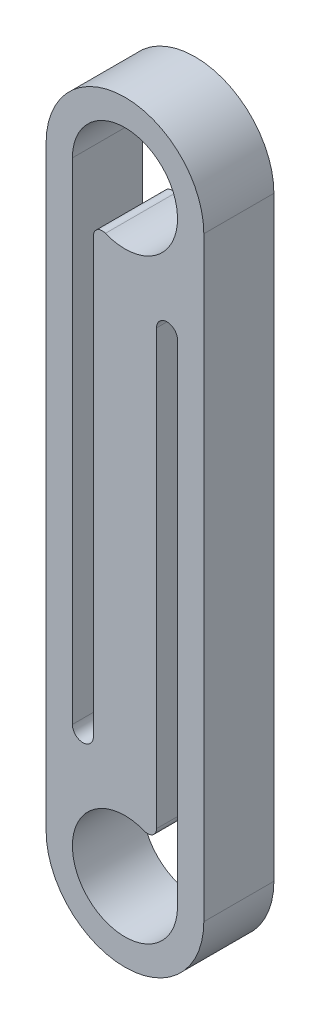
SolidWorks part; units mm, degrees
ref_plane "前视基准面" through (0, 0, 0) normal (0, 0, 1) x (1, 0, 0)
ref_plane "上视基准面" through (0, 0, 0) normal (0, 1, 0) x (1, 0, 0)
ref_plane "右视基准面" through (0, 0, 0) normal (1, 0, 0) x (0, 0, -1)
sketch "草图1" plane through (0, 0, 0) normal (0, 0, 1) x (1, 0, 0)
  line L4 (-4.5, 34) -> (-4.5, 0)
  line L5 (4.5, 34) -> (4.5, 0)
  line L6 (-3, 34) -> (-3, 6)
  line L8 (3, 0) -> (3, 28)
  line L10 (1.8, 28) -> (1.8, 3.2496)
  line L11 (-1.8, 6) -> (-1.8, 30.7504)
  arc A0 (1.1143, 2.7854) -> (3, 0) centre (0, 0) ccw
  arc A1 (-1.1143, 31.2146) -> (-3, 34) centre (0, 34) ccw
  arc A8 (4.5, 34) -> (-4.5, 34) centre (0, 34) ccw
  arc A9 (-4.5, 0) -> (4.5, 0) centre (0, 0) ccw
  arc A10 (1.8, 3.2496) -> (1.1143, 2.7854) centre (1.3, 3.2496) cw
  arc A11 (-1.8, 30.7504) -> (-1.1143, 31.2146) centre (-1.3, 30.7504) cw
  arc A12 (3, 28) -> (1.8, 28) centre (2.4, 28) ccw
  arc A13 (-3, 6) -> (-1.8, 6) centre (-2.4, 6) ccw
  dimension "D2" = 6
  dimension "D3" = 6
  dimension "D4" = 9
  dimension "D5" = 9
  dimension "D7" = 1.2
  dimension "D8" = 28
  dimension "D10" = 0.5
  dimension "D1" = 34
  dimension "D6" = 28
  dimension "D9" = 1.2
extrude "凸台-拉伸1" add sketch "草图1" along normal blind 4
